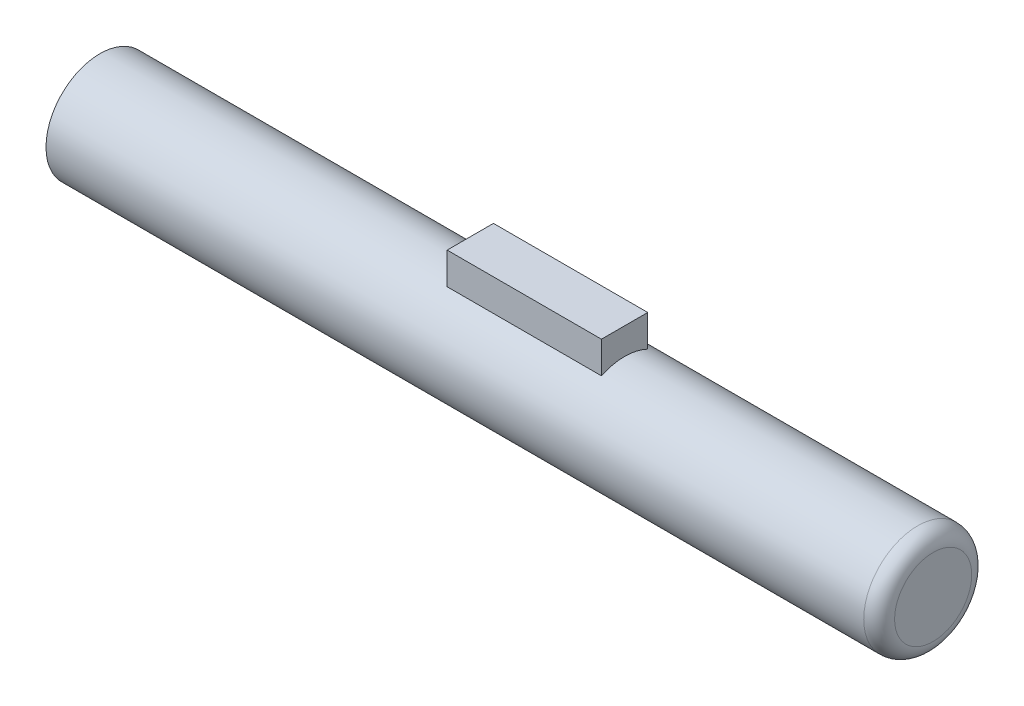
SolidWorks part; units mm, degrees
ref_plane "Ön Düzlem" through (0, 0, 0) normal (0, 0, 1) x (1, 0, 0)
ref_plane "Üst Düzlem" through (0, 0, 0) normal (0, 1, 0) x (1, 0, 0)
ref_plane "Sağ Düzlem" through (0, 0, 0) normal (1, 0, 0) x (0, 0, -1)
sketch "Çizim1" plane through (0, 0, 0) normal (0, 0, 1) x (1, 0, 0)
  line L0 (0, 0) -> (54, 0)
  line L1 (54, 0) -> (54, 3.5)
  line L2 (54, 3.5) -> (0, 3.5)
  line L3 (0, 3.5) -> (0, 0)
  dimension "D1" = 54
  dimension "D2" = 3.5
revolve "Döndür1" add sketch "Çizim1" angle 360 about L0
sketch "Çizim2" plane through (54, 0, 0) normal (1, 0, 0) x (0, 0, -1)
  line L1 (-1.5, 5.22) -> (1.5, 5.22)
  line L2 (-1.5, 5.22) -> (-1.5, 3.1623)
  line L4 (1.5, 5.22) -> (1.5, 3.1623)
  circle A0 centre (0, 0) radius 3.5 construction
  arc A1 (1.5, 3.1623) -> (-1.5, 3.1623) centre (0, 0) ccw
  dimension "D1" = 5.22
  dimension "D2" = 3
extrude "Yükseklik-Ekstrüzyon1" add sketch "Çizim2" against normal blind 10 from offset 20 offset against normal yes
fillet "Radyus1" radius 1 1 edges at (54, 0, 3.5)
